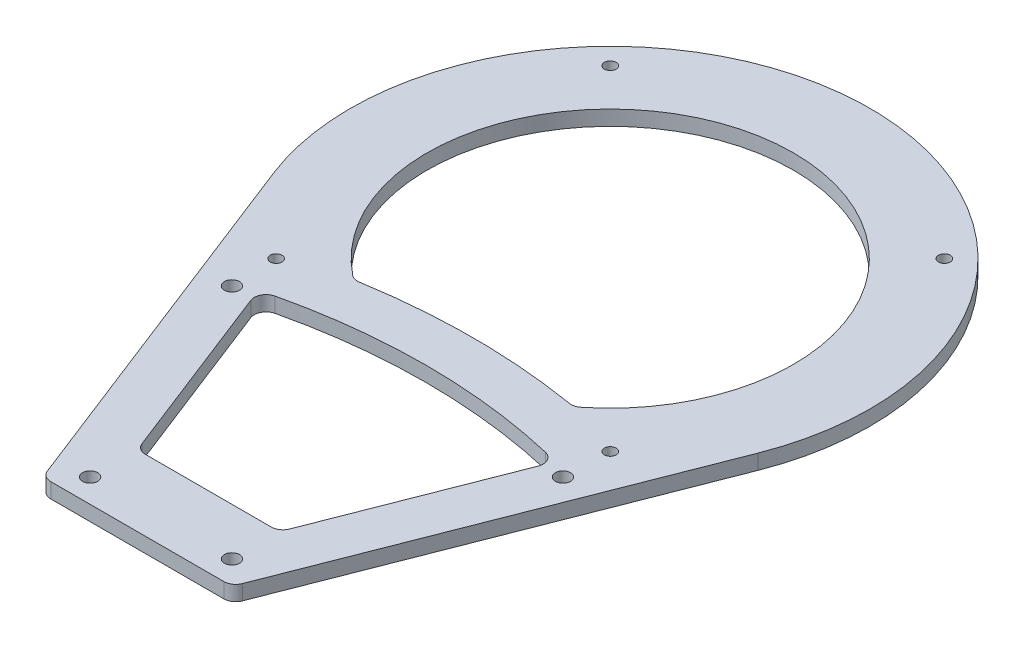
SolidWorks part; units mm, degrees
material "6061 Alloy"
ref_plane "Front Plane" through (0, 0, 0) normal (0, 0, 1) x (1, 0, 0)
ref_plane "Top Plane" through (0, 0, 0) normal (0, 1, 0) x (1, 0, 0)
ref_plane "Right Plane" through (0, 0, 0) normal (1, 0, 0) x (0, 0, -1)
sketch "Sketch1" plane through (0, 0, 0) normal (0, 1, 0) x (1, 0, 0)
  line L1 (-70.6437, 70.6437) -> (70.6437, 70.6437) construction
  line L2 (-70.6437, 70.6437) -> (-70.6438, -70.6437) construction
  line L3 (-70.6438, -70.6437) -> (70.6438, -70.6437) construction
  line L4 (70.6437, 70.6437) -> (70.6438, -70.6437) construction
  line L6 (-102.4669, -40.0066) -> (-40, -200)
  line L7 (-40, -200) -> (40, -200)
  line L8 (40, -200) -> (102.4669, -40.0066)
  line L9 (0, 0) -> (0, -200) construction
  line L10 (-30, -170) -> (30, -170)
  line L11 (30, -170) -> (62.7965, -86)
  line L13 (-62.7965, -86) -> (-30, -170)
  circle A0 centre (0, 0) radius 77.5 construction
  arc A1 (-102.4669, -40.0066) -> (102.4669, -40.0066) centre (0, 0) cw
  circle A2 centre (70.6437, 70.6437) radius 3 construction
  circle A3 centre (-70.6437, 70.6437) radius 3 construction
  circle A4 centre (-70.6438, -70.6437) radius 3 construction
  circle A5 centre (70.6438, -70.6437) radius 3 construction
  circle A6 centre (-30, -190) radius 3 construction
  circle A7 centre (-70, -90) radius 3 construction
  circle A8 centre (30, -190) radius 3 construction
  circle A9 centre (70, -90) radius 3 construction
  arc A10 (-62.7965, -86) -> (62.7965, -86) centre (0, -327.9847) cw
  arc A11 (-46.4794, -62.0154) -> (46.4794, -62.0154) centre (0, -327.9847) cw
  arc A12 (-46.4794, -62.0154) -> (46.4794, -62.0154) centre (0, 0) cw
  point P9 (0, 70.6437)
  point P10 (-70.6437, 0)
  point P18 (0, -200)
  point P35 (0, -170)
  point P36 (0, -77.9847)
  dimension "D1" = 155
  dimension "D3" = 6
  dimension "D4" = 110
  dimension "D8" = 60
  dimension "D9" = 100
  dimension "D10" = 90
  dimension "D11" = 6
  dimension "D12" = 140
  dimension "D13" = 270
  dimension "D7" = 250
  dimension "D2" = 141.2875
  dimension "D5" = 200
  dimension "D6" = 80
  dimension "D14" = 60
  dimension "D15" = 30
  dimension "D16" = 84
extrude "Boss-Extrude1" add sketch "Sketch1" against normal blind 6.35 contours A1 L8 L7 L6
hole_wizard "M6 Clearance Hole1" positions "3DSketch1" profile "Sketch2" hole size "M6" standard "ANSI Metric" end condition through all
sketch3d "3DSketch1"
  point P0 (-70, 0, 90)
  point P2 (-30, 0, 190)
  point P4 (30, 0, 190)
  point P6 (70, 0, 90)
sketch "Sketch2" plane through (-70, 0, 90) normal (1, 0, 0) x (0, 0, 1)
  line L0 (0, 0) -> (0, 6.35)
  line L1 (0, 6.35) -> (3.2, 6.35)
  line L2 (3.2, 6.35) -> (3.2, 0)
  line L5 (3.2, 0) -> (0, 0)
  line L11 (0, -6.35) -> (0, 107.95) construction
  dimension "Thru Hole Dia." = 6.4
  dimension "Thru Hole Depth" = 6.35
hole_wizard "Tap Drill for M6x1.0 Tap1" positions "3DSketch2" profile "Sketch3" hole size "M6x1.0" standard "ANSI Metric" end condition through all
sketch3d "3DSketch2"
  point P0 (-70.6438, 0, 70.6437)
  point P2 (-70.6437, 0, -70.6437)
  point P4 (70.6437, 0, -70.6437)
  point P6 (70.6438, 0, 70.6437)
sketch "Sketch3" plane through (-70.6438, 0, 70.6437) normal (1, 0, 0) x (0, 0, 1)
  line L0 (0, 0) -> (0, 6.35)
  line L1 (0, 6.35) -> (2.5, 6.35)
  line L2 (2.5, 6.35) -> (2.5, 0)
  line L5 (2.5, 0) -> (0, 0)
  line L11 (0, -6.35) -> (0, 107.95) construction
  dimension "Thru Hole Dia." = 5
  dimension "Thru Hole Depth" = 6.35
fillet "Fillet1" radius 5 6 edges at (-30, -3.175, 170) (30, -3.175, 170) (62.7965, -3.175, 86) (-62.7965, -3.175, 86) (-46.4794, -3.175, 62.0154) (46.4794, -3.175, 62.0154)
fillet "Fillet2" radius 5 2 edges at (40, -3.175, 200) (-40, -3.175, 200)
